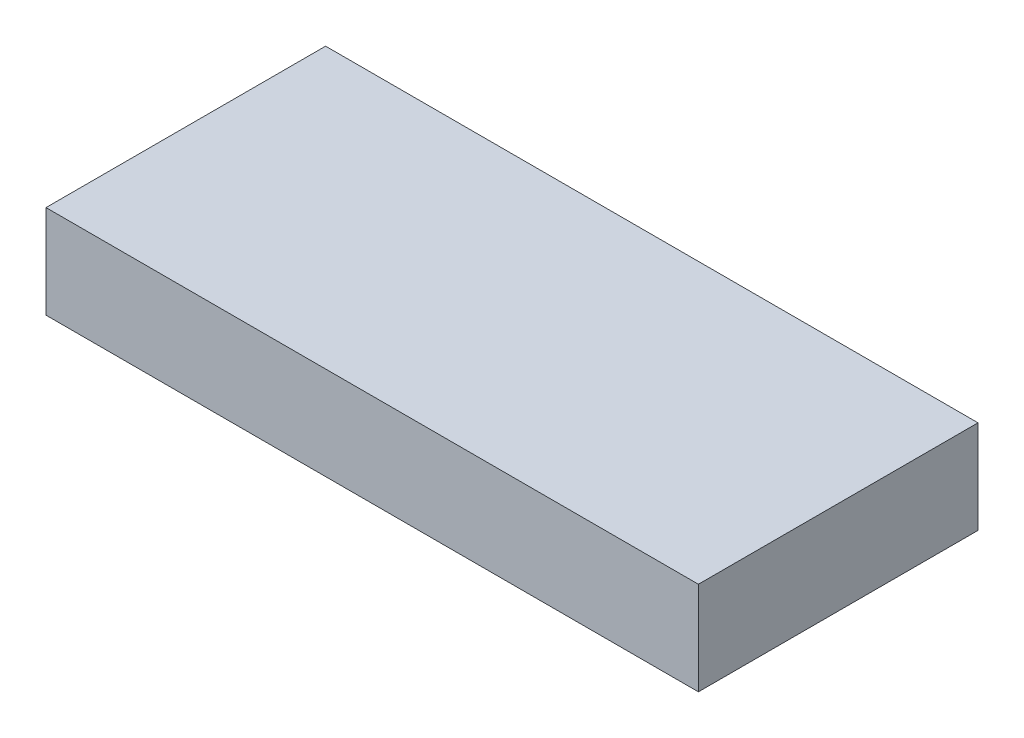
SolidWorks part; units mm, degrees
ref_plane "Front Plane" through (0, 0, 0) normal (0, 0, 1) x (1, 0, 0)
ref_plane "Top Plane" through (0, 0, 0) normal (0, 1, 0) x (1, 0, 0)
ref_plane "Right Plane" through (0, 0, 0) normal (1, 0, 0) x (0, 0, -1)
sketch "Sketch1" plane through (0, 0, 0) normal (0, 1, 0) x (1, 0, 0)
  line L1 (-22.225, -9.525) -> (22.225, -9.525)
  line L2 (-22.225, -9.525) -> (-22.225, 9.525)
  line L3 (-22.225, 9.525) -> (22.225, 9.525)
  line L4 (22.225, -9.525) -> (22.225, 9.525)
  line L5 (-22.225, -9.525) -> (22.225, 9.525) construction
  line L6 (-22.225, 9.525) -> (22.225, -9.525) construction
  point P0 (0, 0)
  dimension "D1" = 44.45
  dimension "D2" = 19.05
extrude "Boss-Extrude1" add sketch "Sketch1" along normal blind 6.35
equation "\"screw-bed-layer-length\"= 1.75in'Clamp left-to-right is barely under."
equation "\"screw-bed-layer-width\"= .75in'Clamp top-to-bottom is just over."
equation "\"material-thickness\"= .25in"
equation "\"D1@Sketch1\" = \"screw-bed-layer-length\""
equation "\"D2@Sketch1\"=\"screw-bed-layer-width\""
equation "\"D1@Boss-Extrude1\"= \"material-thickness\""
